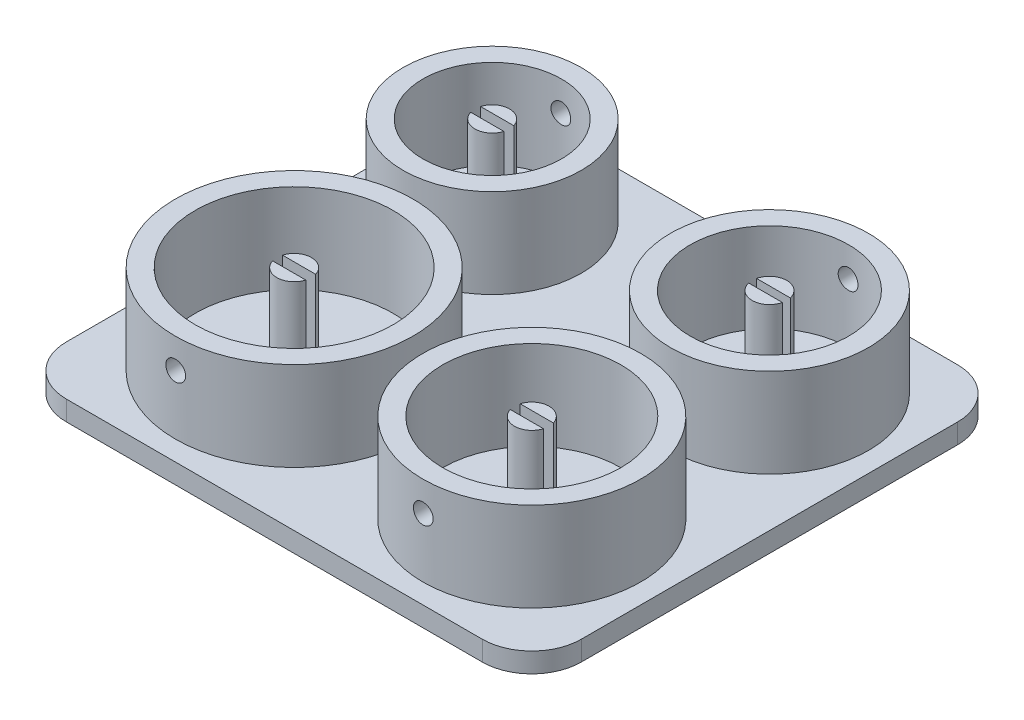
SolidWorks part; units mm, degrees
ref_plane "Front Plane" through (0, 0, 0) normal (0, 0, 1) x (1, 0, 0)
ref_plane "Top Plane" through (0, 0, 0) normal (0, 1, 0) x (1, 0, 0)
ref_plane "Right Plane" through (0, 0, 0) normal (1, 0, 0) x (0, 0, -1)
sketch "Sketch1" plane through (0, 0, 0) normal (0, 1, 0) x (1, 0, 0)
  line L1 (-136.939, -26.0992) -> (-84.939, -26.0992)
  line L2 (-136.939, -26.0992) -> (-136.939, -74.0992)
  line L3 (-136.939, -74.0992) -> (-84.939, -74.0992)
  line L4 (-84.939, -26.0992) -> (-84.939, -74.0992)
extrude "Boss-Extrude3" add sketch "Sketch1" along normal blind 2
sketch "Sketch4" plane through (0, 2, 0) normal (0, 1, 0) x (1, 0, 0)
  circle A0 centre (-125.939, -37.0992) radius 9
  circle A1 centre (-125.939, -37.0992) radius 7
  circle A2 centre (-96.939, -38.0992) radius 10
  circle A3 centre (-96.939, -38.0992) radius 8
  circle A4 centre (-97.939, -61.0992) radius 11
  circle A5 centre (-97.939, -61.0992) radius 9
  circle A6 centre (-122.939, -60.0992) radius 12
  circle A7 centre (-122.939, -60.0992) radius 10
extrude "Boss-Extrude4" add sketch "Sketch4" along normal blind 9
sketch "Sketch5" plane through (0, 2, 0) normal (0, 1, 0) x (1, 0, 0)
  line L0 (-125.939, -37.0992) -> (-125.939, -36.5992)
  line L1 (-125.939, -36.5992) -> (-128.426, -36.5992)
  line L2 (-96.939, -38.0992) -> (-96.939, -37.6992)
  line L3 (-128.426, -36.5992) -> (-123.4029, -36.5992)
  line L4 (-128.426, -36.5992) -> (-128.426, -37.5992)
  line L5 (-128.426, -37.5992) -> (-123.4029, -37.5992)
  line L6 (-123.4029, -36.5992) -> (-123.4029, -37.5992)
  line L7 (-96.939, -37.6992) -> (-99.4413, -37.6992)
  line L8 (-122.939, -60.0992) -> (-122.939, -59.5992)
  line L9 (-99.4413, -37.6992) -> (-94.0944, -37.6992)
  line L10 (-99.4413, -37.6992) -> (-99.4413, -38.4992)
  line L11 (-99.4413, -38.4992) -> (-94.0944, -38.4992)
  line L12 (-94.0944, -37.6992) -> (-94.0944, -38.4992)
  line L13 (-122.939, -59.5992) -> (-125.6472, -59.5992)
  line L14 (-97.939, -61.0992) -> (-97.939, -60.5992)
  line L15 (-125.6472, -59.5992) -> (-119.1091, -59.5992)
  line L16 (-125.6472, -59.5992) -> (-125.6472, -60.5992)
  line L17 (-125.6472, -60.5992) -> (-119.1091, -60.5992)
  line L18 (-119.1091, -59.5992) -> (-119.1091, -60.5992)
  line L19 (-97.939, -60.5992) -> (-100.7165, -60.5992)
  line L21 (-100.7165, -60.5992) -> (-95.2215, -60.5992)
  line L22 (-100.7165, -60.5992) -> (-100.7165, -61.5992)
  line L23 (-100.7165, -61.5992) -> (-95.2215, -61.5992)
  line L24 (-95.2215, -60.5992) -> (-95.2215, -61.5992)
  circle A0 centre (-125.939, -37.0992) radius 1.75
  circle A1 centre (-96.939, -38.0992) radius 1.75
  circle A2 centre (-97.939, -61.0992) radius 1.75
  circle A3 centre (-122.939, -60.0992) radius 1.75
extrude "Boss-Extrude5" add sketch "Sketch5" along normal blind 9 contours L15 A3 L13 | L17 A3 | L21 A2 L19 | L23 A2 | L9 A1 L7 | L11 A1 | L3 A0 L1 | L5 A0
sketch "Sketch6" plane through (0, 0, 74.0992) normal (0, 0, 1) x (1, 0, 0)
  line L0 (-97.939, 2) -> (-97.939, 8)
  line L3 (-136.939, 2) -> (-84.939, 2) construction
  line L4 (-122.939, 2) -> (-122.939, 8)
  circle A0 centre (-97.939, 8) radius 1
  circle A1 centre (-122.939, 8) radius 1
extrude "Cut-Extrude2" cut sketch "Sketch6" against normal blind 6
sketch "Sketch7" plane through (0, 0, 26.0992) normal (0, 0, -1) x (-1, 0, 0)
  line L0 (96.939, 2) -> (96.939, 8)
  line L1 (84.939, 2) -> (136.939, 2) construction
  line L2 (125.939, 2) -> (125.939, 8)
  circle A0 centre (96.939, 8) radius 1
  circle A1 centre (125.939, 8) radius 1
extrude "Cut-Extrude3" cut sketch "Sketch7" against normal blind 6
fillet "Fillet1" radius 5 4 edges at (-136.939, 1, 74.0992) (-136.939, 1, 26.0992) (-84.939, 1, 26.0992) (-84.939, 1, 74.0992)
